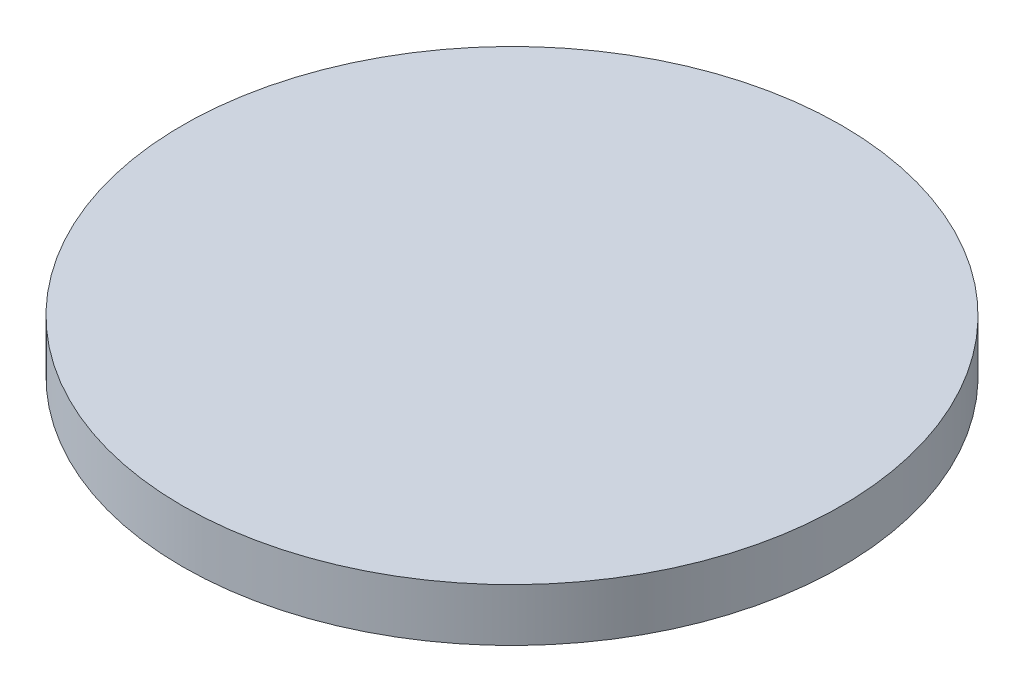
SolidWorks part; units mm, degrees
ref_plane "Front Plane" through (0, 0, 0) normal (0, 0, 1) x (1, 0, 0)
ref_plane "Top Plane" through (0, 0, 0) normal (0, 1, 0) x (1, 0, 0)
ref_plane "Right Plane" through (0, 0, 0) normal (1, 0, 0) x (0, 0, -1)
sketch "Sketch1" plane through (0, 0, 0) normal (0, 1, 0) x (1, 0, 0)
  circle A0 centre (0, 0) radius 6.25
  dimension "D1" = 12.5
extrude "Boss-Extrude1" add sketch "Sketch1" along normal blind 1
